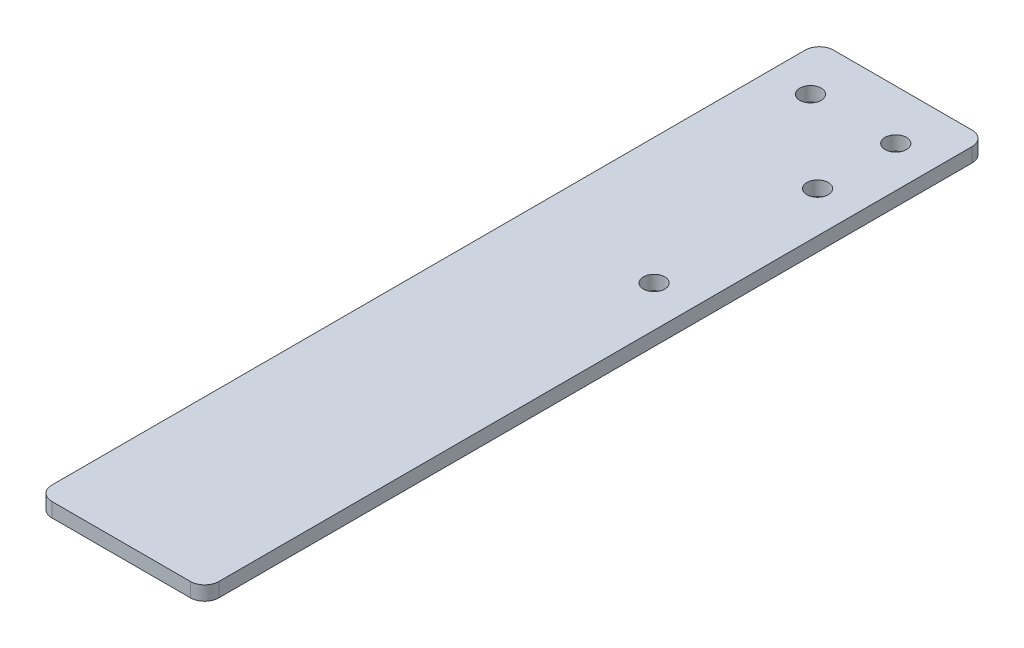
SolidWorks part; units mm, degrees
material "3.0205 (EN-AW 1200)"
ref_plane "Plan de face" through (0, 0, 0) normal (0, 0, 1) x (1, 0, 0)
ref_plane "Plan de dessus" through (0, 0, 0) normal (0, 1, 0) x (1, 0, 0)
ref_plane "Plan de droite" through (0, 0, 0) normal (1, 0, 0) x (0, 0, -1)
sketch "Esquisse1" plane through (0, 0, 0) normal (0, 0, 1) x (1, 0, 0)
  line L1 (0, 0) -> (23.5, 0)
  dimension "D2" = 23.5
extrude "Extru.-Mince1" add sketch "Esquisse1" along normal blind 110 thin thin type one direction reverse wall 2
sketch "Esquisse2" plane through (0, 2, 0) normal (0, 1, 0) x (1, 0, 0)
  line L0 (11.75, 0) -> (11.75, -30.3801) construction
  line L1 (0, 0) -> (23.5, 0) construction
  line L2 (0, -110) -> (0, 0) construction
  circle A0 centre (5.75, -7) radius 1.5
  circle A1 centre (17.75, -18) radius 1.5
  circle A2 centre (17.75, -41) radius 1.5
  circle A3 centre (17.75, -7) radius 1.5
  dimension "D1" = 3
  dimension "D2" = 7
  dimension "D3" = 11
  dimension "D4" = 23
  dimension "D5" = 12
  dimension "D6" = 5.75
extrude "Enlèv. mat.-Extru.1" cut sketch "Esquisse2" against normal through all
fillet "Congé1" radius 2 4 edges at (0, 1, 110) (23.5, 1, 110) (0, 1, 0) (23.5, 1, 0)
